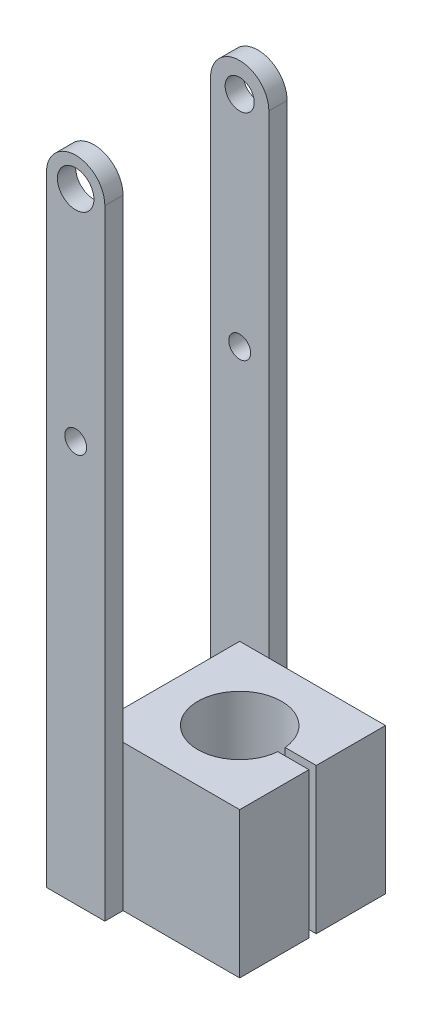
SolidWorks part; units mm, degrees
material "1060 Alloy"
ref_plane "Front Plane" through (0, 0, 0) normal (0, 0, 1) x (1, 0, 0)
ref_plane "Top Plane" through (0, 0, 0) normal (0, 1, 0) x (1, 0, 0)
ref_plane "Right Plane" through (0, 0, 0) normal (1, 0, 0) x (0, 0, -1)
sketch "Sketch2" plane through (0, 0, 0) normal (0, 1, 0) x (1, 0, 0)
  line L0 (-20, 20) -> (20, 20)
  line L1 (20, 20) -> (20, 1)
  line L2 (20, -20) -> (-20, -20)
  line L3 (-20, 20) -> (-20, -20)
  line L5 (11.4564, -1) -> (20, -1)
  line L6 (11.4564, 1) -> (20, 1)
  line L7 (20, -1) -> (20, -20)
  arc A0 (11.4564, 1) -> (11.4564, -1) centre (0, 0) ccw
  dimension "D1" = 20
  dimension "D5" = 23
  dimension "D2" = 40
  dimension "D3" = 20
  dimension "D4" = 40
extrude "Extrude1" add sketch "Sketch2" along normal blind 40
sketch "Sketch3" plane through (0, 0, 20) normal (0, 0, 1) x (1, 0, 0)
  line L0 (-28, 170) -> (-28, 0)
  line L1 (-12, 170) -> (-12, 0)
  line L3 (-20, 40) -> (-20, 0) construction
  line L4 (-20, 0) -> (20, 0)
  line L5 (20, 0) -> (20, 40)
  line L6 (20, 40) -> (-20, 40)
  line L7 (-20, 40) -> (-20, 0)
  line L8 (-28, 0) -> (-12, 0)
  circle A0 centre (-20, 170) radius 5
  arc A1 (-12, 170) -> (-28, 170) centre (-20, 170) ccw
  circle A2 centre (-20, 110) radius 3
  dimension "D5" = 10
  dimension "D8" = 60
  dimension "D2" = 8
  dimension "D9" = 6
  dimension "D3" = 16
  dimension "D4" = 8
  dimension "D6" = 8
  dimension "D7" = 170
  dimension "D1" = 0
extrude "Extrude2" add sketch "Sketch3" along normal blind 5
sketch "Sketch4" plane through (0, 0, -20) normal (0, 0, -1) x (-1, 0, 0)
  line L0 (12, 0) -> (28, 0)
  line L1 (12, 170) -> (12, 0)
  line L2 (28, 0) -> (28, 170)
  circle A0 centre (20, 170) radius 4
  arc A1 (28, 170) -> (12, 170) centre (20, 170) ccw
  circle A2 centre (20, 110) radius 3
  dimension "D2" = 8
  dimension "D5" = 8
  dimension "D3" = 8
  dimension "D4" = 170
  dimension "D6" = 6
  dimension "D7" = 60
  dimension "D1" = 16
extrude "Extrude3" add sketch "Sketch4" along normal blind 5
